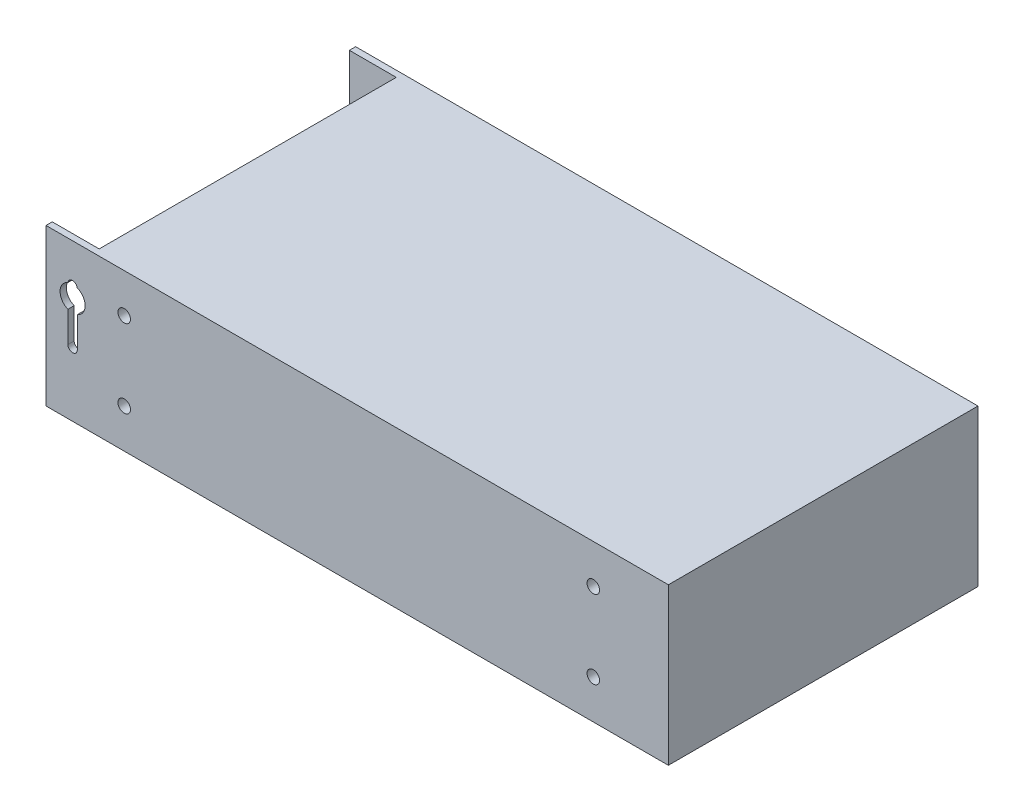
SolidWorks part; units mm, degrees
ref_plane "前视基准面" through (0, 0, 0) normal (0, 0, 1) x (1, 0, 0)
ref_plane "上视基准面" through (0, 0, 0) normal (0, 1, 0) x (1, 0, 0)
ref_plane "右视基准面" through (0, 0, 0) normal (1, 0, 0) x (0, 0, -1)
sketch "草图1" plane through (0, 0, 0) normal (0, 1, 0) x (1, 0, 0)
  line L1 (111.2506, 47.9881) -> (-87.7494, 47.9881)
  line L2 (111.2506, 47.9881) -> (111.2506, -51.0119)
  line L3 (111.2506, -51.0119) -> (-87.7494, -51.0119)
  line L4 (-87.7494, 47.9881) -> (-87.7494, -51.0119)
extrude "凸台-拉伸1" add sketch "草图1" along normal blind 9
sketch "草图2" plane through (0, 9, 0) normal (0, 1, 0) x (1, 0, 0)
  line L0 (-87.7494, 47.9881) -> (-87.7494, -51.0119) construction
  line L1 (111.2506, -51.0119) -> (-87.7494, -51.0119)
  line L2 (111.2506, -51.0119) -> (111.2506, -49.0119)
  line L3 (111.2506, -49.0119) -> (-87.7494, -49.0119)
  line L4 (-87.7494, -51.0119) -> (-87.7494, -49.0119)
extrude "凸台-拉伸2" add sketch "草图2" along normal blind 41
sketch "草图4" plane through (0, 9, 0) normal (0, 1, 0) x (1, 0, 0)
  line L0 (111.2506, -49.0119) -> (111.2506, 47.9881) construction
  line L1 (-87.7494, 47.9881) -> (111.2506, 47.9881)
  line L2 (-87.7494, 47.9881) -> (-87.7494, 45.9881)
  line L3 (-87.7494, 45.9881) -> (111.2506, 45.9881)
  line L4 (111.2506, 47.9881) -> (111.2506, 45.9881)
extrude "凸台-拉伸3" add sketch "草图4" along normal blind 41
sketch "草图5" plane through (0, 9, 0) normal (0, 1, 0) x (1, 0, 0)
  line L0 (111.2506, -49.0119) -> (-87.7494, -49.0119) construction
  line L1 (111.2506, 45.9881) -> (-72.7494, 45.9881)
  line L2 (111.2506, 45.9881) -> (111.2506, -49.0119)
  line L3 (111.2506, -49.0119) -> (-72.7494, -49.0119)
  line L4 (-72.7494, 45.9881) -> (-72.7494, -49.0119)
extrude "凸台-拉伸4" add sketch "草图5" along normal blind 41
sketch "草图6" plane through (0, 0, 51.0119) normal (0, 0, 1) x (1, 0, 0)
  line L0 (111.2506, 50) -> (87.2506, 50)
  line L1 (-87.7494, 50) -> (111.2506, 50) construction
  line L2 (87.2506, 50) -> (87.2506, 37.5)
  line L3 (111.2506, 0) -> (87.2506, 0)
  line L4 (-87.7494, 0) -> (111.2506, 0) construction
  line L5 (87.2506, 0) -> (87.2506, 12.5)
  line L6 (-87.7494, 0) -> (-62.7494, 0)
  line L7 (-62.7494, 0) -> (-62.7494, 12.5)
  line L8 (-87.7494, 50) -> (-62.7494, 50)
  line L9 (-62.7494, 50) -> (-62.7494, 37.5)
  circle A0 centre (87.2506, 37.5) radius 2
  circle A1 centre (87.2506, 12.5) radius 2
  circle A2 centre (-62.7494, 12.5) radius 2
  circle A3 centre (-62.7494, 37.5) radius 2
extrude "切除-拉伸2" cut sketch "草图6" against normal blind 10 contours A3 | A2 | A0 | A1
sketch "草图8" plane through (0, 0, 51.0119) normal (0, 0, 1) x (1, 0, 0)
  line L0 (-87.7494, 50) -> (-79.2494, 50)
  line L1 (-87.7494, 50) -> (111.2506, 50) construction
  line L2 (-79.2494, 50) -> (-79.2494, 34)
  line L5 (-77.7494, 20.5) -> (-77.7494, 37.5)
  line L6 (-80.7494, 20.5) -> (-80.7494, 37.5)
  circle A0 centre (-79.2494, 37.5) radius 1.5
  circle A1 centre (-79.2494, 20.5) radius 1.5
  circle A2 centre (-79.2494, 34) radius 4
extrude "切除-拉伸3" cut sketch "草图8" against normal blind 10
sketch "草图9" plane through (0, 0, 51.0119) normal (0, 0, 1) x (1, 0, 0)
sketch "草图10" plane through (0, 0, -47.9881) normal (0, 0, -1) x (-1, 0, 0)
  circle A0 centre (62.7494, 12.5) radius 2
  circle A1 centre (-87.2506, 12.5) radius 2
extrude "切除-拉伸4" cut sketch "草图10" against normal through all
sketch "草图11" plane through (0, 0, 0) normal (0, -1, 0) x (-1, 0, 0)
  circle A0 centre (72.7494, 23.4881) radius 1.5
  circle A1 centre (72.7494, -26.5119) radius 1.5
  circle A2 centre (-77.2506, 23.4881) radius 1.5
  circle A3 centre (-77.2506, -26.5119) radius 1.5
extrude "切除-拉伸5" cut sketch "草图11" against normal blind 6 contours A1 | A0 | A2 | A3
